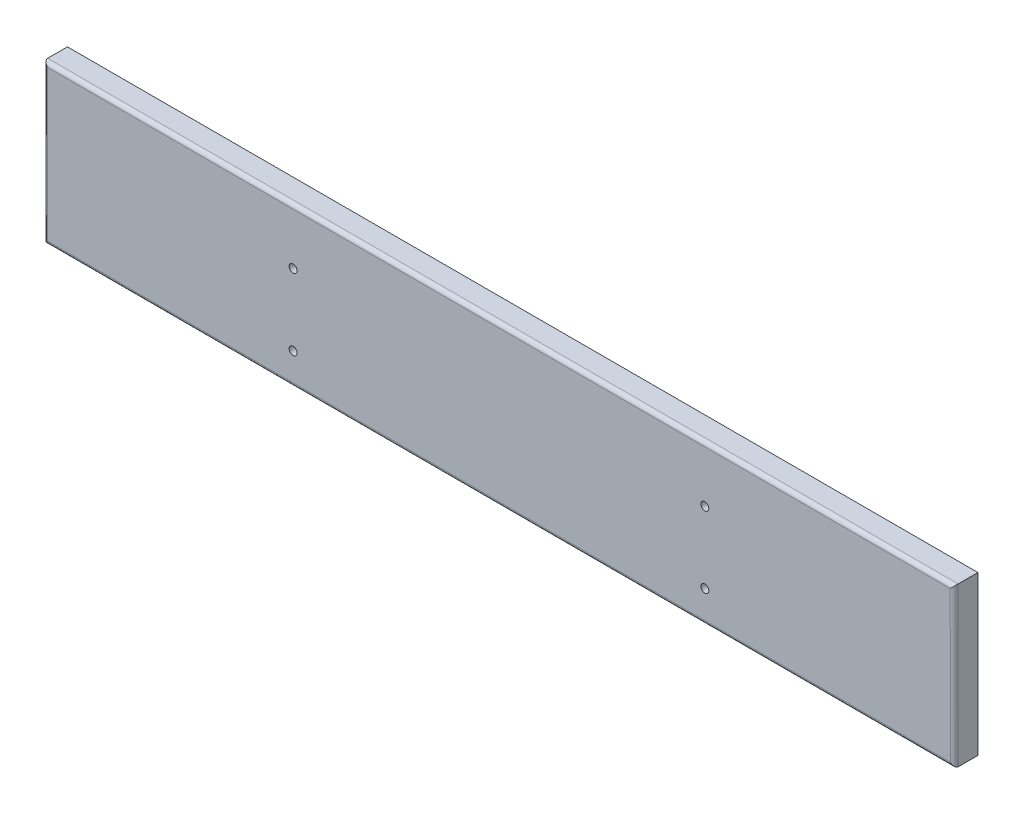
SolidWorks part; units mm, degrees
material "Pine"
ref_plane "Front Plane" through (0, 0, 0) normal (0, 0, 1) x (1, 0, 0)
ref_plane "Top Plane" through (0, 0, 0) normal (0, 1, 0) x (1, 0, 0)
ref_plane "Right Plane" through (0, 0, 0) normal (1, 0, 0) x (0, 0, -1)
sketch "Sketch1" plane through (0, 0, -348.1825) normal (0, 0, 1) x (1, 0, 0)
  line L4 (378.7978, 164.4834) -> (-351.4522, 164.4834)
  line L6 (-351.4522, 37.4834) -> (378.8386, 37.4834)
  line L7 (-351.4522, 164.4834) -> (-351.4522, 37.4834)
  line L8 (378.7978, 164.4834) -> (378.8386, 37.4834)
extrude "Boss-Extrude1" add sketch "Sketch1" along normal blind 19.05 contours L8 L4 L7 L6
sketch "Sketch6" plane through (0, 0, -348.1825) normal (0, 0, -1) x (-1, 0, 0)
  line L0 (-378.8386, 37.4834) -> (-178.8136, 37.4834) construction
  line L1 (351.4522, 37.4834) -> (-378.8386, 37.4834) construction
  line L2 (-178.8136, 37.4834) -> (-178.8136, 62.8834) construction
  line L3 (-178.8136, 62.8834) -> (-178.8136, 120.0334) construction
  line L4 (-178.8136, 37.4834) -> (151.3864, 37.4834) construction
  line L5 (151.3864, 37.4834) -> (151.3864, 62.8834) construction
  line L6 (151.3864, 62.8834) -> (151.3864, 120.0334) construction
hole_wizard "1/4 (0.25) Diameter Hole1" positions "Sketch4" profile "Sketch5" hole size "1/4" standard "ANSI Inch" end condition through all
sketch "Sketch4" plane through (0, 0, -329.1325) normal (0, 0, 1) x (1, 0, 0)
  point P12 (-151.3864, 120.0334)
  point P15 (-151.3864, 62.8834)
  point P18 (178.8136, 62.8834)
  point P21 (178.8136, 120.0334)
sketch "Sketch5" plane through (-151.3864, 120.0334, -329.1325) normal (1, 0, 0) x (0, -1, 0)
  line L0 (0, 0) -> (0, 19.05)
  line L1 (0, 19.05) -> (3.937, 19.05)
  line L2 (3.175, 18.1734) -> (3.175, 0)
  line L5 (3.175, 0) -> (0, 0)
  line L7 (3.937, 19.05) -> (3.175, 18.1734)
  line L8 (-3.937, 19.05) -> (-3.175, 18.1734) construction
  line L11 (0, -6.35) -> (0, 107.95) construction
  dimension "Thru Hole Dia." = 6.35
  dimension "Thru Hole Depth" = 19.05
  dimension "Far C'Sink Dia." = 7.874
  dimension "Far C'Sink Angle" = 82
fillet "Fillet1" radius 3.175 4 edges at (-351.4522, 100.9834, -329.1325) (13.6932, 37.4834, -329.1325) (378.8182, 100.9834, -329.1325) (13.6728, 164.4834, -329.1325)
